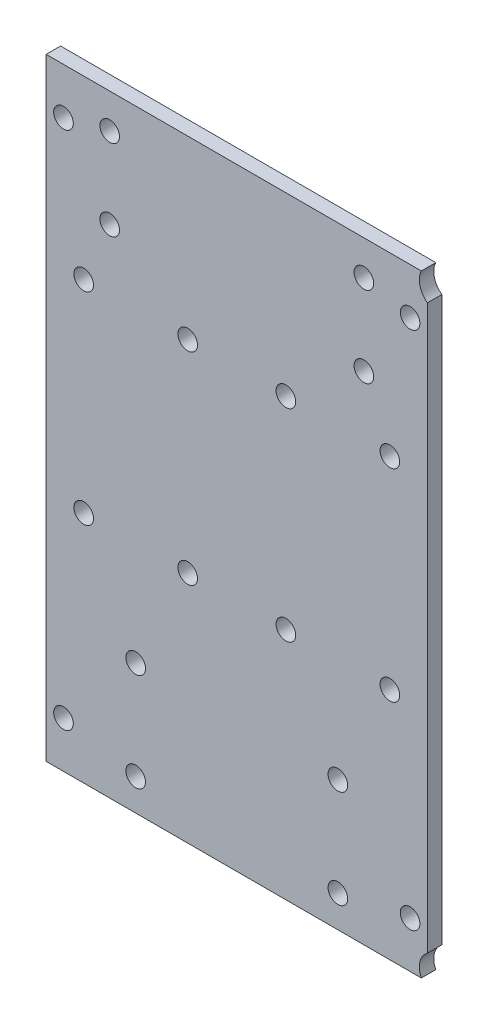
SolidWorks part; units mm, degrees
other "Controller Shelf"
ref_plane "Front Plane" through (0, 0, 0) normal (0, 0, 1) x (1, 0, 0)
ref_plane "Top Plane" through (0, 0, 0) normal (0, 1, 0) x (1, 0, 0)
ref_plane "Right Plane" through (0, 0, 0) normal (1, 0, 0) x (0, 0, -1)
sketch3d "Main Profile Sketch datum points"
  point P0 (0, 0, 69)
  point P1 (10, 0, 69)
  point P2 (0, 10, 69)
ref_plane "Main Profile Sketch plane" through (0, 0, 69) normal (0, 0, 1) x (1, 0, 0)
sketch "Main Profile Sketch" plane through (0, 0, 69) normal (0, 0, 1) x (1, 0, 0)
  line L0 (-158, 53) -> (-93.0512, 53)
  line L1 (-92, 48.7505) -> (-92, -48.7505)
  line L2 (-158, -53) -> (-93.0512, -53)
  line L3 (-158, 53) -> (-158, -53)
  arc A0 (-93.0512, 53) -> (-92, 48.7505) centre (-90, 51.5) ccw
  arc A1 (-92, -48.7505) -> (-93.0512, -53) centre (-90, -51.5) ccw
  circle A2 centre (-155, -45) radius 1.7
  circle A3 centre (-142.5, -47.5) radius 1.7
  circle A4 centre (-142.5, -30.5) radius 1.7
  circle A5 centre (-151.5, -12.5) radius 1.7
  circle A6 centre (-133.5, -12.5) radius 1.7
  circle A7 centre (-107.5, -47.5) radius 1.7
  circle A8 centre (-95, -45) radius 1.7
  circle A9 centre (-107.5, -30.5) radius 1.7
  circle A10 centre (-116.5, -12.5) radius 1.7
  circle A11 centre (-98.5, -12.5) radius 1.7
  circle A12 centre (-151.5, 22.5) radius 1.7
  circle A13 centre (-133.5, 22.5) radius 1.7
  circle A14 centre (-147, 33) radius 1.7
  circle A15 centre (-155, 45) radius 1.7
  circle A16 centre (-147, 47) radius 1.7
  circle A17 centre (-116.5, 22.5) radius 1.7
  circle A18 centre (-98.5, 22.5) radius 1.7
  circle A19 centre (-103, 33) radius 1.7
  circle A20 centre (-103, 47) radius 1.7
  circle A21 centre (-95, 45) radius 1.7
extrude "Main Extrusion" add sketch "Main Profile Sketch" against normal blind 2.5 separate body
